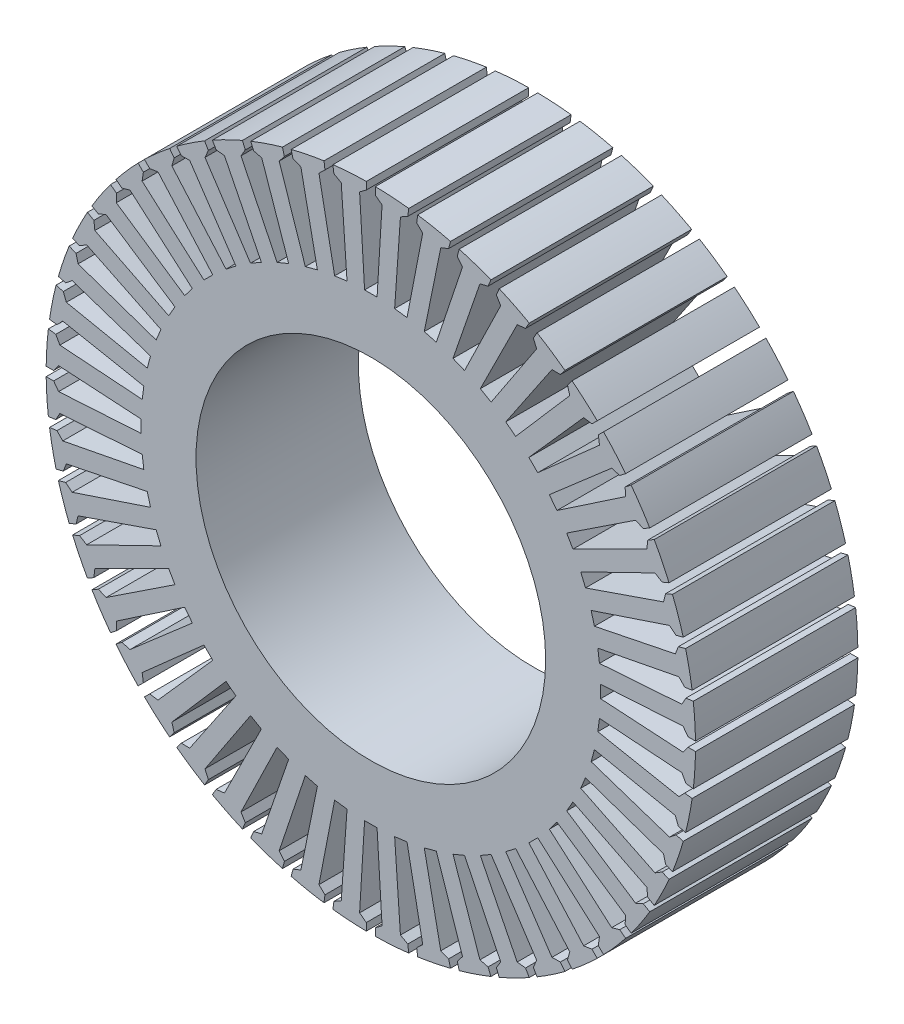
SolidWorks part; units mm, degrees
ref_plane "Спереди" through (0, 0, 0) normal (0, 0, 1) x (1, 0, 0)
ref_plane "Сверху" through (0, 0, 0) normal (0, 1, 0) x (1, 0, 0)
ref_plane "Справа" through (0, 0, 0) normal (1, 0, 0) x (0, 0, -1)
sketch "Эскиз1" plane through (0, 0, 0) normal (0, 0, 1) x (1, 0, 0)
  circle A0 centre (0, 0) radius 60
  circle A1 centre (0, 0) radius 32.3077
extrude "Stator_stack" add sketch "Эскиз1" along normal blind 30 from offset 15
sketch "Эскиз2" plane through (0, 0, 0) normal (0, 0, 1) x (1, 0, 0)
  line L0 (60.9943, -0.8308) -> (58.6154, -0.8308)
  line L1 (58.6154, -0.8308) -> (57.6923, -2.0769)
  line L2 (57.6923, -2.0769) -> (42.4615, -1.1538)
  line L3 (42.4615, -1.1538) -> (42.4615, 1.1538)
  line L4 (42.4615, 1.1538) -> (57.6923, 2.0769)
  line L5 (57.6923, 2.0769) -> (58.6154, 0.8308)
  line L6 (58.6154, 0.8308) -> (60.9943, 0.8308)
  line L7 (60.9943, 0.8308) -> (60.9943, -0.8308)
  line L8 (60.581, 7.1377) -> (58.2224, 6.8272)
  line L9 (58.2224, 6.8272) -> (57.4698, 5.4712)
  line L10 (57.4698, 5.4712) -> (42.2489, 4.3984)
  line L11 (42.2489, 4.3984) -> (41.9477, 6.6863)
  line L12 (41.9477, 6.6863) -> (56.9276, 9.5895)
  line L13 (56.9276, 9.5895) -> (58.0055, 8.4745)
  line L14 (58.0055, 8.4745) -> (60.3641, 8.785)
  line L15 (60.3641, 8.785) -> (60.581, 7.1377)
  line L16 (59.131, 14.984) -> (56.8331, 14.3683)
  line L17 (56.8331, 14.3683) -> (56.264, 12.9257)
  line L18 (56.264, 12.9257) -> (41.3133, 9.8753)
  line L19 (41.3133, 9.8753) -> (40.7161, 12.1044)
  line L20 (40.7161, 12.1044) -> (55.1889, 16.938)
  line L21 (55.1889, 16.938) -> (56.4031, 15.9732)
  line L22 (56.4031, 15.9732) -> (58.701, 16.589)
  line L23 (58.701, 16.589) -> (59.131, 14.984)
  line L24 (56.6693, 22.574) -> (54.4715, 21.6636)
  line L25 (54.4715, 21.6636) -> (54.0955, 20.1591)
  line L26 (54.0955, 20.1591) -> (39.6709, 15.1833)
  line L27 (39.6709, 15.1833) -> (38.7878, 17.3153)
  line L28 (38.7878, 17.3153) -> (52.5059, 23.9967)
  line L29 (52.5059, 23.9967) -> (53.8356, 23.1987)
  line L30 (53.8356, 23.1987) -> (56.0335, 24.1091)
  line L31 (56.0335, 24.1091) -> (56.6693, 22.574)
  line L32 (53.238, 29.7777) -> (51.1778, 28.5882)
  line L33 (51.1778, 28.5882) -> (51.0015, 27.0475)
  line L34 (51.0015, 27.0475) -> (37.3497, 20.2315)
  line L35 (37.3497, 20.2315) -> (36.1958, 22.23)
  line L36 (36.1958, 22.23) -> (48.9245, 30.6448)
  line L37 (48.9245, 30.6448) -> (50.347, 30.0272)
  line L38 (50.347, 30.0272) -> (52.4073, 31.2166)
  line L39 (52.4073, 31.2166) -> (53.238, 29.7777)
  line L40 (48.8958, 36.4719) -> (47.0085, 35.0237)
  line L41 (47.0085, 35.0237) -> (47.0347, 33.4731)
  line L42 (47.0347, 33.4731) -> (34.3894, 24.9335)
  line L43 (34.3894, 24.9335) -> (32.9846, 26.7644)
  line L44 (32.9846, 26.7644) -> (44.506, 36.7686)
  line L45 (44.506, 36.7686) -> (45.997, 36.3419)
  line L46 (45.997, 36.3419) -> (47.8843, 37.7901)
  line L47 (47.8843, 37.7901) -> (48.8958, 36.4719)
  line L48 (43.717, 42.5421) -> (42.0348, 40.8599)
  line L49 (42.0348, 40.8599) -> (42.2632, 39.326)
  line L50 (42.2632, 39.326) -> (30.8407, 29.2089)
  line L51 (30.8407, 29.2089) -> (29.2089, 30.8407)
  line L52 (29.2089, 30.8407) -> (39.326, 42.2632)
  line L53 (39.326, 42.2632) -> (40.8599, 42.0348)
  line L54 (40.8599, 42.0348) -> (42.5421, 43.717)
  line L55 (42.5421, 43.717) -> (43.717, 42.5421)
  line L56 (37.7901, 47.8843) -> (36.3419, 45.997)
  line L57 (36.3419, 45.997) -> (36.7686, 44.506)
  line L58 (36.7686, 44.506) -> (26.7644, 32.9846)
  line L59 (26.7644, 32.9846) -> (24.9335, 34.3894)
  line L60 (24.9335, 34.3894) -> (33.4731, 47.0347)
  line L61 (33.4731, 47.0347) -> (35.0237, 47.0085)
  line L62 (35.0237, 47.0085) -> (36.4719, 48.8958)
  line L63 (36.4719, 48.8958) -> (37.7901, 47.8843)
  line L64 (31.2166, 52.4073) -> (30.0272, 50.347)
  line L65 (30.0272, 50.347) -> (30.6448, 48.9245)
  line L66 (30.6448, 48.9245) -> (22.23, 36.1958)
  line L67 (22.23, 36.1958) -> (20.2315, 37.3497)
  line L68 (20.2315, 37.3497) -> (27.0475, 51.0015)
  line L69 (27.0475, 51.0015) -> (28.5882, 51.1778)
  line L70 (28.5882, 51.1778) -> (29.7777, 53.238)
  line L71 (29.7777, 53.238) -> (31.2166, 52.4073)
  line L72 (24.1091, 56.0335) -> (23.1987, 53.8356)
  line L73 (23.1987, 53.8356) -> (23.9967, 52.5059)
  line L74 (23.9967, 52.5059) -> (17.3153, 38.7878)
  line L75 (17.3153, 38.7878) -> (15.1833, 39.6709)
  line L76 (15.1833, 39.6709) -> (20.1591, 54.0955)
  line L77 (20.1591, 54.0955) -> (21.6636, 54.4715)
  line L78 (21.6636, 54.4715) -> (22.574, 56.6693)
  line L79 (22.574, 56.6693) -> (24.1091, 56.0335)
  line L80 (16.589, 58.701) -> (15.9732, 56.4031)
  line L81 (15.9732, 56.4031) -> (16.938, 55.1889)
  line L82 (16.938, 55.1889) -> (12.1044, 40.7161)
  line L83 (12.1044, 40.7161) -> (9.8753, 41.3133)
  line L84 (9.8753, 41.3133) -> (12.9257, 56.264)
  line L85 (12.9257, 56.264) -> (14.3683, 56.8331)
  line L86 (14.3683, 56.8331) -> (14.984, 59.131)
  line L87 (14.984, 59.131) -> (16.589, 58.701)
  line L88 (8.785, 60.3641) -> (8.4745, 58.0055)
  line L89 (8.4745, 58.0055) -> (9.5895, 56.9276)
  line L90 (9.5895, 56.9276) -> (6.6863, 41.9477)
  line L91 (6.6863, 41.9477) -> (4.3984, 42.2489)
  line L92 (4.3984, 42.2489) -> (5.4712, 57.4698)
  line L93 (5.4712, 57.4698) -> (6.8272, 58.2224)
  line L94 (6.8272, 58.2224) -> (7.1377, 60.581)
  line L95 (7.1377, 60.581) -> (8.785, 60.3641)
  line L96 (0.8308, 60.9943) -> (0.8308, 58.6154)
  line L97 (0.8308, 58.6154) -> (2.0769, 57.6923)
  line L98 (2.0769, 57.6923) -> (1.1538, 42.4615)
  line L99 (1.1538, 42.4615) -> (-1.1538, 42.4615)
  line L100 (-1.1538, 42.4615) -> (-2.0769, 57.6923)
  line L101 (-2.0769, 57.6923) -> (-0.8308, 58.6154)
  line L102 (-0.8308, 58.6154) -> (-0.8308, 60.9943)
  line L103 (-0.8308, 60.9943) -> (0.8308, 60.9943)
  line L104 (-7.1377, 60.581) -> (-6.8272, 58.2224)
  line L105 (-6.8272, 58.2224) -> (-5.4712, 57.4698)
  line L106 (-5.4712, 57.4698) -> (-4.3984, 42.2489)
  line L107 (-4.3984, 42.2489) -> (-6.6863, 41.9477)
  line L108 (-6.6863, 41.9477) -> (-9.5895, 56.9276)
  line L109 (-9.5895, 56.9276) -> (-8.4745, 58.0055)
  line L110 (-8.4745, 58.0055) -> (-8.785, 60.3641)
  line L111 (-8.785, 60.3641) -> (-7.1377, 60.581)
  line L112 (-14.984, 59.131) -> (-14.3683, 56.8331)
  line L113 (-14.3683, 56.8331) -> (-12.9257, 56.264)
  line L114 (-12.9257, 56.264) -> (-9.8753, 41.3133)
  line L115 (-9.8753, 41.3133) -> (-12.1044, 40.7161)
  line L116 (-12.1044, 40.7161) -> (-16.938, 55.1889)
  line L117 (-16.938, 55.1889) -> (-15.9732, 56.4031)
  line L118 (-15.9732, 56.4031) -> (-16.589, 58.701)
  line L119 (-16.589, 58.701) -> (-14.984, 59.131)
  line L120 (-22.574, 56.6693) -> (-21.6636, 54.4715)
  line L121 (-21.6636, 54.4715) -> (-20.1591, 54.0955)
  line L122 (-20.1591, 54.0955) -> (-15.1833, 39.6709)
  line L123 (-15.1833, 39.6709) -> (-17.3153, 38.7878)
  line L124 (-17.3153, 38.7878) -> (-23.9967, 52.5059)
  line L125 (-23.9967, 52.5059) -> (-23.1987, 53.8356)
  line L126 (-23.1987, 53.8356) -> (-24.1091, 56.0335)
  line L127 (-24.1091, 56.0335) -> (-22.574, 56.6693)
  line L128 (-29.7777, 53.238) -> (-28.5882, 51.1778)
  line L129 (-28.5882, 51.1778) -> (-27.0475, 51.0015)
  line L130 (-27.0475, 51.0015) -> (-20.2315, 37.3497)
  line L131 (-20.2315, 37.3497) -> (-22.23, 36.1958)
  line L132 (-22.23, 36.1958) -> (-30.6448, 48.9245)
  line L133 (-30.6448, 48.9245) -> (-30.0272, 50.347)
  line L134 (-30.0272, 50.347) -> (-31.2166, 52.4073)
  line L135 (-31.2166, 52.4073) -> (-29.7777, 53.238)
  line L136 (-36.4719, 48.8958) -> (-35.0237, 47.0085)
  line L137 (-35.0237, 47.0085) -> (-33.4731, 47.0347)
  line L138 (-33.4731, 47.0347) -> (-24.9335, 34.3894)
  line L139 (-24.9335, 34.3894) -> (-26.7644, 32.9846)
  line L140 (-26.7644, 32.9846) -> (-36.7686, 44.506)
  line L141 (-36.7686, 44.506) -> (-36.3419, 45.997)
  line L142 (-36.3419, 45.997) -> (-37.7901, 47.8843)
  line L143 (-37.7901, 47.8843) -> (-36.4719, 48.8958)
  line L144 (-42.5421, 43.717) -> (-40.8599, 42.0348)
  line L145 (-40.8599, 42.0348) -> (-39.326, 42.2632)
  line L146 (-39.326, 42.2632) -> (-29.2089, 30.8407)
  line L147 (-29.2089, 30.8407) -> (-30.8407, 29.2089)
  line L148 (-30.8407, 29.2089) -> (-42.2632, 39.326)
  line L149 (-42.2632, 39.326) -> (-42.0348, 40.8599)
  line L150 (-42.0348, 40.8599) -> (-43.717, 42.5421)
  line L151 (-43.717, 42.5421) -> (-42.5421, 43.717)
  line L152 (-47.8843, 37.7901) -> (-45.997, 36.3419)
  line L153 (-45.997, 36.3419) -> (-44.506, 36.7686)
  line L154 (-44.506, 36.7686) -> (-32.9846, 26.7644)
  line L155 (-32.9846, 26.7644) -> (-34.3894, 24.9335)
  line L156 (-34.3894, 24.9335) -> (-47.0347, 33.4731)
  line L157 (-47.0347, 33.4731) -> (-47.0085, 35.0237)
  line L158 (-47.0085, 35.0237) -> (-48.8958, 36.4719)
  line L159 (-48.8958, 36.4719) -> (-47.8843, 37.7901)
  line L160 (-52.4073, 31.2166) -> (-50.347, 30.0272)
  line L161 (-50.347, 30.0272) -> (-48.9245, 30.6448)
  line L162 (-48.9245, 30.6448) -> (-36.1958, 22.23)
  line L163 (-36.1958, 22.23) -> (-37.3497, 20.2315)
  line L164 (-37.3497, 20.2315) -> (-51.0015, 27.0475)
  line L165 (-51.0015, 27.0475) -> (-51.1778, 28.5882)
  line L166 (-51.1778, 28.5882) -> (-53.238, 29.7777)
  line L167 (-53.238, 29.7777) -> (-52.4073, 31.2166)
  line L168 (-56.0335, 24.1091) -> (-53.8356, 23.1987)
  line L169 (-53.8356, 23.1987) -> (-52.5059, 23.9967)
  line L170 (-52.5059, 23.9967) -> (-38.7878, 17.3153)
  line L171 (-38.7878, 17.3153) -> (-39.6709, 15.1833)
  line L172 (-39.6709, 15.1833) -> (-54.0955, 20.1591)
  line L173 (-54.0955, 20.1591) -> (-54.4715, 21.6636)
  line L174 (-54.4715, 21.6636) -> (-56.6693, 22.574)
  line L175 (-56.6693, 22.574) -> (-56.0335, 24.1091)
  line L176 (-58.701, 16.589) -> (-56.4031, 15.9732)
  line L177 (-56.4031, 15.9732) -> (-55.1889, 16.938)
  line L178 (-55.1889, 16.938) -> (-40.7161, 12.1044)
  line L179 (-40.7161, 12.1044) -> (-41.3133, 9.8753)
  line L180 (-41.3133, 9.8753) -> (-56.264, 12.9257)
  line L181 (-56.264, 12.9257) -> (-56.8331, 14.3683)
  line L182 (-56.8331, 14.3683) -> (-59.131, 14.984)
  line L183 (-59.131, 14.984) -> (-58.701, 16.589)
  line L184 (-60.3641, 8.785) -> (-58.0055, 8.4745)
  line L185 (-58.0055, 8.4745) -> (-56.9276, 9.5895)
  line L186 (-56.9276, 9.5895) -> (-41.9477, 6.6863)
  line L187 (-41.9477, 6.6863) -> (-42.2489, 4.3984)
  line L188 (-42.2489, 4.3984) -> (-57.4698, 5.4712)
  line L189 (-57.4698, 5.4712) -> (-58.2224, 6.8272)
  line L190 (-58.2224, 6.8272) -> (-60.581, 7.1377)
  line L191 (-60.581, 7.1377) -> (-60.3641, 8.785)
  line L192 (-60.9943, 0.8308) -> (-58.6154, 0.8308)
  line L193 (-58.6154, 0.8308) -> (-57.6923, 2.0769)
  line L194 (-57.6923, 2.0769) -> (-42.4615, 1.1538)
  line L195 (-42.4615, 1.1538) -> (-42.4615, -1.1538)
  line L196 (-42.4615, -1.1538) -> (-57.6923, -2.0769)
  line L197 (-57.6923, -2.0769) -> (-58.6154, -0.8308)
  line L198 (-58.6154, -0.8308) -> (-60.9943, -0.8308)
  line L199 (-60.9943, -0.8308) -> (-60.9943, 0.8308)
  line L200 (-60.581, -7.1377) -> (-58.2224, -6.8272)
  line L201 (-58.2224, -6.8272) -> (-57.4698, -5.4712)
  line L202 (-57.4698, -5.4712) -> (-42.2489, -4.3984)
  line L203 (-42.2489, -4.3984) -> (-41.9477, -6.6863)
  line L204 (-41.9477, -6.6863) -> (-56.9276, -9.5895)
  line L205 (-56.9276, -9.5895) -> (-58.0055, -8.4745)
  line L206 (-58.0055, -8.4745) -> (-60.3641, -8.785)
  line L207 (-60.3641, -8.785) -> (-60.581, -7.1377)
  line L208 (-59.131, -14.984) -> (-56.8331, -14.3683)
  line L209 (-56.8331, -14.3683) -> (-56.264, -12.9257)
  line L210 (-56.264, -12.9257) -> (-41.3133, -9.8753)
  line L211 (-41.3133, -9.8753) -> (-40.7161, -12.1044)
  line L212 (-40.7161, -12.1044) -> (-55.1889, -16.938)
  line L213 (-55.1889, -16.938) -> (-56.4031, -15.9732)
  line L214 (-56.4031, -15.9732) -> (-58.701, -16.589)
  line L215 (-58.701, -16.589) -> (-59.131, -14.984)
  line L216 (-56.6693, -22.574) -> (-54.4715, -21.6636)
  line L217 (-54.4715, -21.6636) -> (-54.0955, -20.1591)
  line L218 (-54.0955, -20.1591) -> (-39.6709, -15.1833)
  line L219 (-39.6709, -15.1833) -> (-38.7878, -17.3153)
  line L220 (-38.7878, -17.3153) -> (-52.5059, -23.9967)
  line L221 (-52.5059, -23.9967) -> (-53.8356, -23.1987)
  line L222 (-53.8356, -23.1987) -> (-56.0335, -24.1091)
  line L223 (-56.0335, -24.1091) -> (-56.6693, -22.574)
  line L224 (-53.238, -29.7777) -> (-51.1778, -28.5882)
  line L225 (-51.1778, -28.5882) -> (-51.0015, -27.0475)
  line L226 (-51.0015, -27.0475) -> (-37.3497, -20.2315)
  line L227 (-37.3497, -20.2315) -> (-36.1958, -22.23)
  line L228 (-36.1958, -22.23) -> (-48.9245, -30.6448)
  line L229 (-48.9245, -30.6448) -> (-50.347, -30.0272)
  line L230 (-50.347, -30.0272) -> (-52.4073, -31.2166)
  line L231 (-52.4073, -31.2166) -> (-53.238, -29.7777)
  line L232 (-48.8958, -36.4719) -> (-47.0085, -35.0237)
  line L233 (-47.0085, -35.0237) -> (-47.0347, -33.4731)
  line L234 (-47.0347, -33.4731) -> (-34.3894, -24.9335)
  line L235 (-34.3894, -24.9335) -> (-32.9846, -26.7644)
  line L236 (-32.9846, -26.7644) -> (-44.506, -36.7686)
  line L237 (-44.506, -36.7686) -> (-45.997, -36.3419)
  line L238 (-45.997, -36.3419) -> (-47.8843, -37.7901)
  line L239 (-47.8843, -37.7901) -> (-48.8958, -36.4719)
  line L240 (-43.717, -42.5421) -> (-42.0348, -40.8599)
  line L241 (-42.0348, -40.8599) -> (-42.2632, -39.326)
  line L242 (-42.2632, -39.326) -> (-30.8407, -29.2089)
  line L243 (-30.8407, -29.2089) -> (-29.2089, -30.8407)
  line L244 (-29.2089, -30.8407) -> (-39.326, -42.2632)
  line L245 (-39.326, -42.2632) -> (-40.8599, -42.0348)
  line L246 (-40.8599, -42.0348) -> (-42.5421, -43.717)
  line L247 (-42.5421, -43.717) -> (-43.717, -42.5421)
  line L248 (-37.7901, -47.8843) -> (-36.3419, -45.997)
  line L249 (-36.3419, -45.997) -> (-36.7686, -44.506)
  line L250 (-36.7686, -44.506) -> (-26.7644, -32.9846)
  line L251 (-26.7644, -32.9846) -> (-24.9335, -34.3894)
  line L252 (-24.9335, -34.3894) -> (-33.4731, -47.0347)
  line L253 (-33.4731, -47.0347) -> (-35.0237, -47.0085)
  line L254 (-35.0237, -47.0085) -> (-36.4719, -48.8958)
  line L255 (-36.4719, -48.8958) -> (-37.7901, -47.8843)
  line L256 (-31.2166, -52.4073) -> (-30.0272, -50.347)
  line L257 (-30.0272, -50.347) -> (-30.6448, -48.9245)
  line L258 (-30.6448, -48.9245) -> (-22.23, -36.1958)
  line L259 (-22.23, -36.1958) -> (-20.2315, -37.3497)
  line L260 (-20.2315, -37.3497) -> (-27.0475, -51.0015)
  line L261 (-27.0475, -51.0015) -> (-28.5882, -51.1778)
  line L262 (-28.5882, -51.1778) -> (-29.7777, -53.238)
  line L263 (-29.7777, -53.238) -> (-31.2166, -52.4073)
  line L264 (-24.1091, -56.0335) -> (-23.1987, -53.8356)
  line L265 (-23.1987, -53.8356) -> (-23.9967, -52.5059)
  line L266 (-23.9967, -52.5059) -> (-17.3153, -38.7878)
  line L267 (-17.3153, -38.7878) -> (-15.1833, -39.6709)
  line L268 (-15.1833, -39.6709) -> (-20.1591, -54.0955)
  line L269 (-20.1591, -54.0955) -> (-21.6636, -54.4715)
  line L270 (-21.6636, -54.4715) -> (-22.574, -56.6693)
  line L271 (-22.574, -56.6693) -> (-24.1091, -56.0335)
  line L272 (-16.589, -58.701) -> (-15.9732, -56.4031)
  line L273 (-15.9732, -56.4031) -> (-16.938, -55.1889)
  line L274 (-16.938, -55.1889) -> (-12.1044, -40.7161)
  line L275 (-12.1044, -40.7161) -> (-9.8753, -41.3133)
  line L276 (-9.8753, -41.3133) -> (-12.9257, -56.264)
  line L277 (-12.9257, -56.264) -> (-14.3683, -56.8331)
  line L278 (-14.3683, -56.8331) -> (-14.984, -59.131)
  line L279 (-14.984, -59.131) -> (-16.589, -58.701)
  line L280 (-8.785, -60.3641) -> (-8.4745, -58.0055)
  line L281 (-8.4745, -58.0055) -> (-9.5895, -56.9276)
  line L282 (-9.5895, -56.9276) -> (-6.6863, -41.9477)
  line L283 (-6.6863, -41.9477) -> (-4.3984, -42.2489)
  line L284 (-4.3984, -42.2489) -> (-5.4712, -57.4698)
  line L285 (-5.4712, -57.4698) -> (-6.8272, -58.2224)
  line L286 (-6.8272, -58.2224) -> (-7.1377, -60.581)
  line L287 (-7.1377, -60.581) -> (-8.785, -60.3641)
  line L288 (-0.8308, -60.9943) -> (-0.8308, -58.6154)
  line L289 (-0.8308, -58.6154) -> (-2.0769, -57.6923)
  line L290 (-2.0769, -57.6923) -> (-1.1538, -42.4615)
  line L291 (-1.1538, -42.4615) -> (1.1538, -42.4615)
  line L292 (1.1538, -42.4615) -> (2.0769, -57.6923)
  line L293 (2.0769, -57.6923) -> (0.8308, -58.6154)
  line L294 (0.8308, -58.6154) -> (0.8308, -60.9943)
  line L295 (0.8308, -60.9943) -> (-0.8308, -60.9943)
  line L296 (7.1377, -60.581) -> (6.8272, -58.2224)
  line L297 (6.8272, -58.2224) -> (5.4712, -57.4698)
  line L298 (5.4712, -57.4698) -> (4.3984, -42.2489)
  line L299 (4.3984, -42.2489) -> (6.6863, -41.9477)
  line L300 (6.6863, -41.9477) -> (9.5895, -56.9276)
  line L301 (9.5895, -56.9276) -> (8.4745, -58.0055)
  line L302 (8.4745, -58.0055) -> (8.785, -60.3641)
  line L303 (8.785, -60.3641) -> (7.1377, -60.581)
  line L304 (14.984, -59.131) -> (14.3683, -56.8331)
  line L305 (14.3683, -56.8331) -> (12.9257, -56.264)
  line L306 (12.9257, -56.264) -> (9.8753, -41.3133)
  line L307 (9.8753, -41.3133) -> (12.1044, -40.7161)
  line L308 (12.1044, -40.7161) -> (16.938, -55.1889)
  line L309 (16.938, -55.1889) -> (15.9732, -56.4031)
  line L310 (15.9732, -56.4031) -> (16.589, -58.701)
  line L311 (16.589, -58.701) -> (14.984, -59.131)
  line L312 (22.574, -56.6693) -> (21.6636, -54.4715)
  line L313 (21.6636, -54.4715) -> (20.1591, -54.0955)
  line L314 (20.1591, -54.0955) -> (15.1833, -39.6709)
  line L315 (15.1833, -39.6709) -> (17.3153, -38.7878)
  line L316 (17.3153, -38.7878) -> (23.9967, -52.5059)
  line L317 (23.9967, -52.5059) -> (23.1987, -53.8356)
  line L318 (23.1987, -53.8356) -> (24.1091, -56.0335)
  line L319 (24.1091, -56.0335) -> (22.574, -56.6693)
  line L320 (29.7777, -53.238) -> (28.5882, -51.1778)
  line L321 (28.5882, -51.1778) -> (27.0475, -51.0015)
  line L322 (27.0475, -51.0015) -> (20.2315, -37.3497)
  line L323 (20.2315, -37.3497) -> (22.23, -36.1958)
  line L324 (22.23, -36.1958) -> (30.6448, -48.9245)
  line L325 (30.6448, -48.9245) -> (30.0272, -50.347)
  line L326 (30.0272, -50.347) -> (31.2166, -52.4073)
  line L327 (31.2166, -52.4073) -> (29.7777, -53.238)
  line L328 (36.4719, -48.8958) -> (35.0237, -47.0085)
  line L329 (35.0237, -47.0085) -> (33.4731, -47.0347)
  line L330 (33.4731, -47.0347) -> (24.9335, -34.3894)
  line L331 (24.9335, -34.3894) -> (26.7644, -32.9846)
  line L332 (26.7644, -32.9846) -> (36.7686, -44.506)
  line L333 (36.7686, -44.506) -> (36.3419, -45.997)
  line L334 (36.3419, -45.997) -> (37.7901, -47.8843)
  line L335 (37.7901, -47.8843) -> (36.4719, -48.8958)
  line L336 (42.5421, -43.717) -> (40.8599, -42.0348)
  line L337 (40.8599, -42.0348) -> (39.326, -42.2632)
  line L338 (39.326, -42.2632) -> (29.2089, -30.8407)
  line L339 (29.2089, -30.8407) -> (30.8407, -29.2089)
  line L340 (30.8407, -29.2089) -> (42.2632, -39.326)
  line L341 (42.2632, -39.326) -> (42.0348, -40.8599)
  line L342 (42.0348, -40.8599) -> (43.717, -42.5421)
  line L343 (43.717, -42.5421) -> (42.5421, -43.717)
  line L344 (47.8843, -37.7901) -> (45.997, -36.3419)
  line L345 (45.997, -36.3419) -> (44.506, -36.7686)
  line L346 (44.506, -36.7686) -> (32.9846, -26.7644)
  line L347 (32.9846, -26.7644) -> (34.3894, -24.9335)
  line L348 (34.3894, -24.9335) -> (47.0347, -33.4731)
  line L349 (47.0347, -33.4731) -> (47.0085, -35.0237)
  line L350 (47.0085, -35.0237) -> (48.8958, -36.4719)
  line L351 (48.8958, -36.4719) -> (47.8843, -37.7901)
  line L352 (52.4073, -31.2166) -> (50.347, -30.0272)
  line L353 (50.347, -30.0272) -> (48.9245, -30.6448)
  line L354 (48.9245, -30.6448) -> (36.1958, -22.23)
  line L355 (36.1958, -22.23) -> (37.3497, -20.2315)
  line L356 (37.3497, -20.2315) -> (51.0015, -27.0475)
  line L357 (51.0015, -27.0475) -> (51.1778, -28.5882)
  line L358 (51.1778, -28.5882) -> (53.238, -29.7777)
  line L359 (53.238, -29.7777) -> (52.4073, -31.2166)
  line L360 (56.0335, -24.1091) -> (53.8356, -23.1987)
  line L361 (53.8356, -23.1987) -> (52.5059, -23.9967)
  line L362 (52.5059, -23.9967) -> (38.7878, -17.3153)
  line L363 (38.7878, -17.3153) -> (39.6709, -15.1833)
  line L364 (39.6709, -15.1833) -> (54.0955, -20.1591)
  line L365 (54.0955, -20.1591) -> (54.4715, -21.6636)
  line L366 (54.4715, -21.6636) -> (56.6693, -22.574)
  line L367 (56.6693, -22.574) -> (56.0335, -24.1091)
  line L368 (58.701, -16.589) -> (56.4031, -15.9732)
  line L369 (56.4031, -15.9732) -> (55.1889, -16.938)
  line L370 (55.1889, -16.938) -> (40.7161, -12.1044)
  line L371 (40.7161, -12.1044) -> (41.3133, -9.8753)
  line L372 (41.3133, -9.8753) -> (56.264, -12.9257)
  line L373 (56.264, -12.9257) -> (56.8331, -14.3683)
  line L374 (56.8331, -14.3683) -> (59.131, -14.984)
  line L375 (59.131, -14.984) -> (58.701, -16.589)
  line L376 (60.3641, -8.785) -> (58.0055, -8.4745)
  line L377 (58.0055, -8.4745) -> (56.9276, -9.5895)
  line L378 (56.9276, -9.5895) -> (41.9477, -6.6863)
  line L379 (41.9477, -6.6863) -> (42.2489, -4.3984)
  line L380 (42.2489, -4.3984) -> (57.4698, -5.4712)
  line L381 (57.4698, -5.4712) -> (58.2224, -6.8272)
  line L382 (58.2224, -6.8272) -> (60.581, -7.1377)
  line L383 (60.581, -7.1377) -> (60.3641, -8.785)
extrude "Stator_48_slots" cut sketch "Эскиз2" against normal mid plane 32
